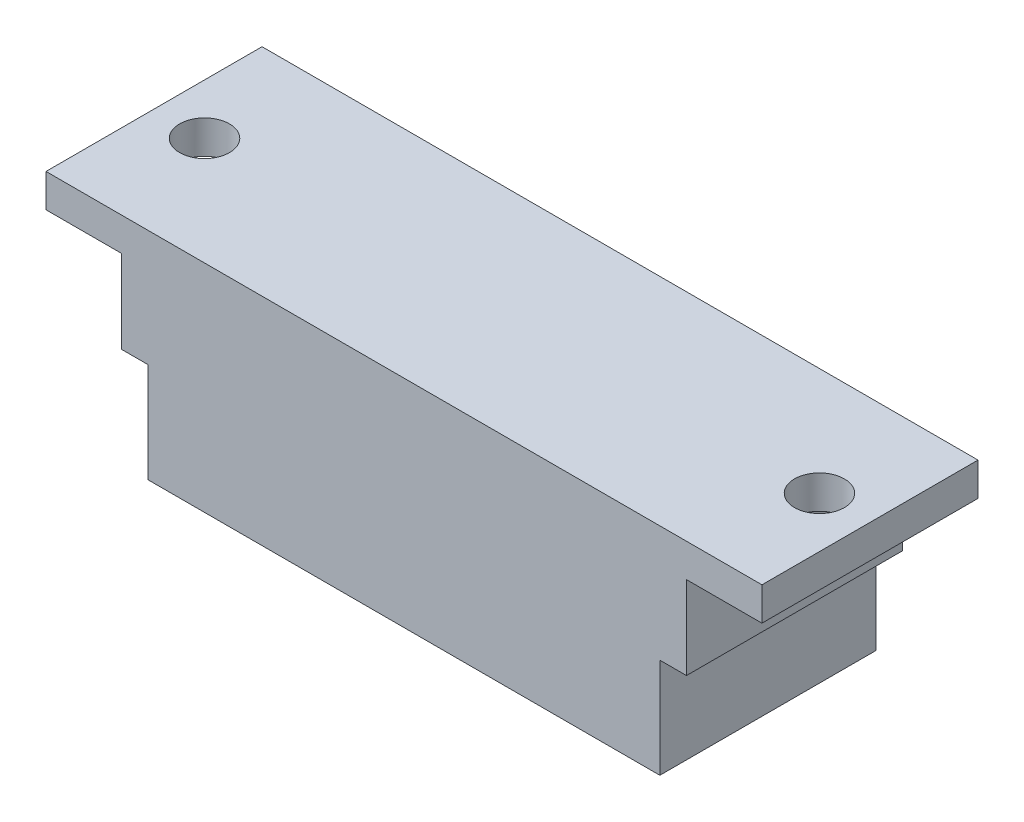
SolidWorks part; units mm, degrees
ref_plane "前视基准面" through (0, 0, 0) normal (0, 0, 1) x (1, 0, 0)
ref_plane "上视基准面" through (0, 0, 0) normal (0, 1, 0) x (1, 0, 0)
ref_plane "右视基准面" through (0, 0, 0) normal (1, 0, 0) x (0, 0, -1)
sketch "草图1" plane through (0, 0, 0) normal (0, 0, 1) x (1, 0, 0)
  line L0 (0, 8.9426) -> (0, -12.7834) construction
  line L1 (-21.5407, 5.292) -> (21.5407, 5.292)
  line L2 (21.5407, 5.292) -> (21.5407, 3.292)
  line L3 (21.5407, 3.292) -> (16.9996, 3.292)
  line L4 (16.9996, 3.292) -> (16.9996, -1.708)
  line L5 (16.9996, -1.708) -> (15.3968, -1.708)
  line L6 (15.3968, -1.708) -> (15.3968, -7.708)
  line L7 (15.3968, -7.708) -> (-15.3968, -7.708)
  line L8 (-15.3968, -1.708) -> (-15.3968, -7.708)
  line L9 (-16.9996, -1.708) -> (-15.3968, -1.708)
  line L10 (-16.9996, 3.292) -> (-16.9996, -1.708)
  line L11 (-21.5407, 3.292) -> (-16.9996, 3.292)
  line L12 (-21.5407, 5.292) -> (-21.5407, 3.292)
  point P12 (0, -7.708)
  point P17 (0, 5.292)
  dimension "D1" = 13
  dimension "D2" = 2
  dimension "D3" = 6
extrude "凸台-拉伸1" add sketch "草图1" along normal blind 13
sketch "草图2" plane through (0, 5.292, 0) normal (0, 1, 0) x (1, 0, 0)
  line L0 (0, -13) -> (0, 0) construction
  line L1 (21.5407, -13) -> (-21.5407, -13) construction
  line L2 (-21.5407, -6.5) -> (21.5407, -6.5) construction
  line L3 (-21.5407, -13) -> (-21.5407, 0) construction
  line L4 (21.5407, -13) -> (21.5407, 0) construction
  circle A0 centre (-18.5, -6.5) radius 1.5
  circle A1 centre (18.5, -6.5) radius 1.5
  dimension "D1" = 37
extrude "切除-拉伸1" cut sketch "草图2" against normal through all
